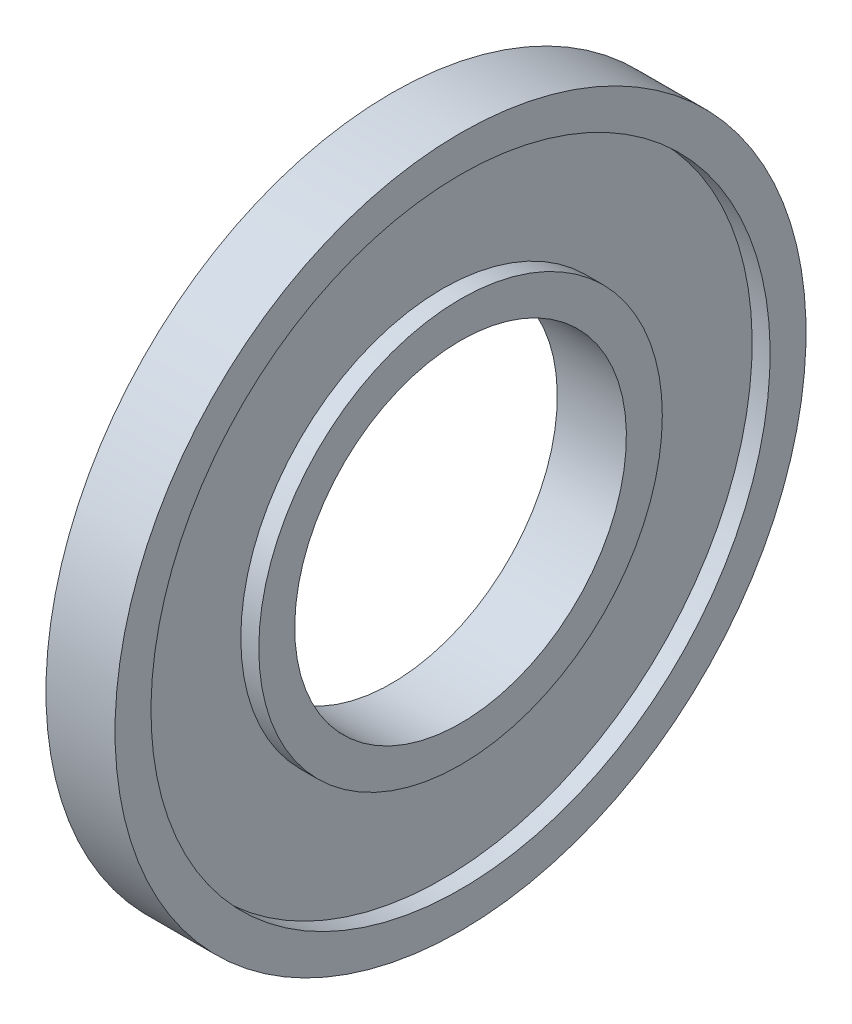
SolidWorks part; units mm, degrees
material "Plain Carbon Steel"
ref_plane "Front Plane" through (0, 0, 0) normal (0, 0, 1) x (1, 0, 0)
ref_plane "Top Plane" through (0, 0, 0) normal (0, 1, 0) x (1, 0, 0)
ref_plane "Right Plane" through (0, 0, 0) normal (1, 0, 0) x (0, 0, -1)
other "Configuration Table"
sketch "Sketch1" plane through (0, 0, 0) normal (0, 0, 1) x (1, 0, 0)
  line L0 (6.4812, 0) -> (0, 0) construction
  line L1 (-2.5, 25) -> (2.5, 25)
  line L2 (2.5, 25) -> (2.5, 22.4)
  line L3 (2.5, 22.4) -> (1.2, 22.4)
  line L4 (1.2, 22.4) -> (1.2, 14.6)
  line L5 (1.2, 14.6) -> (2.5, 14.6)
  line L6 (2.5, 14.6) -> (2.5, 12)
  line L7 (2.5, 12) -> (-2.5, 12)
  line L8 (0, 12) -> (0, 25) construction
  line L9 (0, 25) -> (0, 0) construction
  line L10 (-2.5, 14.6) -> (-2.5, 12)
  line L11 (-1.2, 14.6) -> (-2.5, 14.6)
  line L12 (-1.2, 22.4) -> (-1.2, 14.6)
  line L13 (-2.5, 22.4) -> (-1.2, 22.4)
  line L14 (-2.5, 25) -> (-2.5, 22.4)
  line L15 (1.2, 14.6) -> (1.2, 13.3) construction
  line L16 (2.5, 14.6) -> (2.5, 17.2) construction
  line L17 (2.5, 17.2) -> (2.5, 19.8) construction
  line L18 (2.5, 19.8) -> (2.5, 22.4) construction
  point P21 (2.5, 13.3)
revolve "Revolve1" add sketch "Sketch1" angle 360 about L0
equation "\"d_i\" = 50"
equation "\"OD@Sketch1\" = \"d_i\""
equation "\"d_o\" = 24"
equation "\"w\" = 5"
equation "\"Thickness@Sketch1\" = \"w\""
equation "\"ID@Sketch1\" = \"d_o\""
